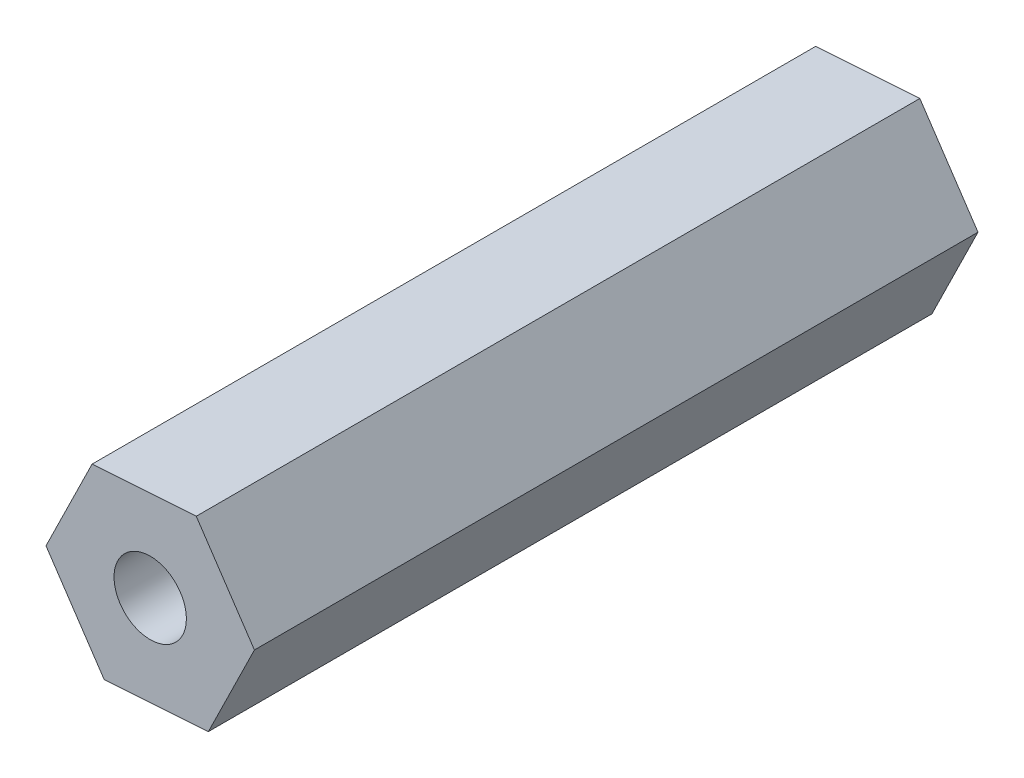
SolidWorks part; units mm, degrees
ref_plane "Front Plane" through (0, 0, 0) normal (0, 0, 1) x (1, 0, 0)
ref_plane "Top Plane" through (0, 0, 0) normal (0, 1, 0) x (1, 0, 0)
ref_plane "Right Plane" through (0, 0, 0) normal (1, 0, 0) x (0, 0, -1)
sketch "Sketch1" plane through (0, 0, 0) normal (0, 0, 1) x (1, 0, 0)
  line L1 (4.0831, -6.0903) -> (7.3159, 0.4909)
  line L2 (7.3159, 0.4909) -> (3.2328, 6.5812)
  line L3 (3.2328, 6.5812) -> (-4.0831, 6.0903)
  line L4 (-4.0831, 6.0903) -> (-7.3159, -0.4909)
  line L5 (-7.3159, -0.4909) -> (-3.2328, -6.5812)
  line L6 (-3.2328, -6.5812) -> (4.0831, -6.0903)
  circle A0 centre (0, 0) radius 6.35 construction
  circle A1 centre (0, 0) radius 2.54
  dimension "D2" = 5.08
  dimension "D1" = 12.7
extrude "Boss-Extrude1" add sketch "Sketch1" along normal blind 50.8
